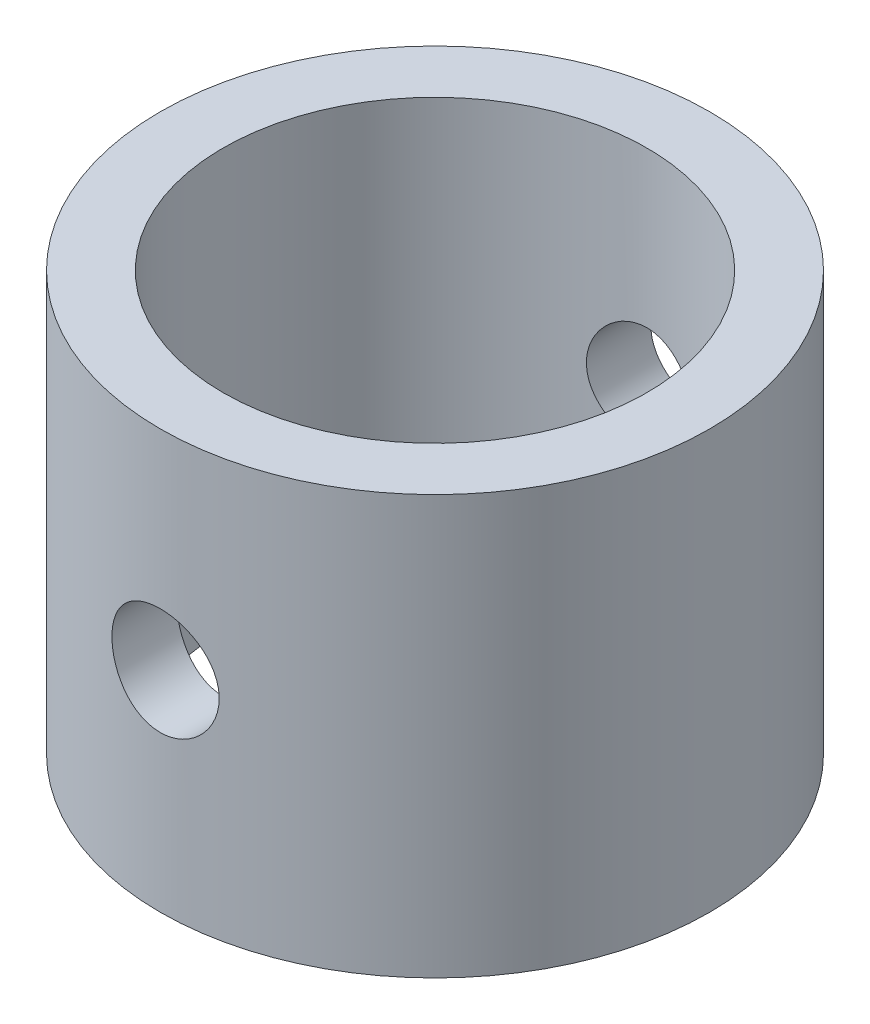
SolidWorks part; units mm, degrees
ref_plane "Front Plane" through (0, 0, 0) normal (0, 0, 1) x (1, 0, 0)
ref_plane "Top Plane" through (0, 0, 0) normal (0, 1, 0) x (1, 0, 0)
ref_plane "Right Plane" through (0, 0, 0) normal (1, 0, 0) x (0, 0, -1)
sketch "Sketch1" plane through (0, 0, 0) normal (0, 1, 0) x (1, 0, 0)
  circle A0 centre (0, 0) radius 4.05
  circle A1 centre (0, 0) radius 5.25
  dimension "D1" = 10.5
  dimension "D2" = 8.1
extrude "Boss-Extrude1" add sketch "Sketch1" along normal mid plane 8
sketch "Sketch3" plane through (0, 0, 0) normal (0, 0, 1) x (1, 0, 0)
  circle A0 centre (0, 0) radius 1.025
  dimension "D1" = 2.05
extrude "Cut-Extrude1" cut sketch "Sketch3" against normal through all both and the other way through all
sketch "Sketch4" plane through (0, 0, 0) normal (0, 0, 1) x (1, 0, 0)
  circle A0 centre (0, 0) radius 1.025
sketch "Sketch6" plane through (0, 0, 0) normal (0, 1, 0) x (1, 0, 0)
  line L0 (0, 3.4531) -> (0, -2.9155)
  line L1 (-2.7983, 0) -> (2.7983, 0)
